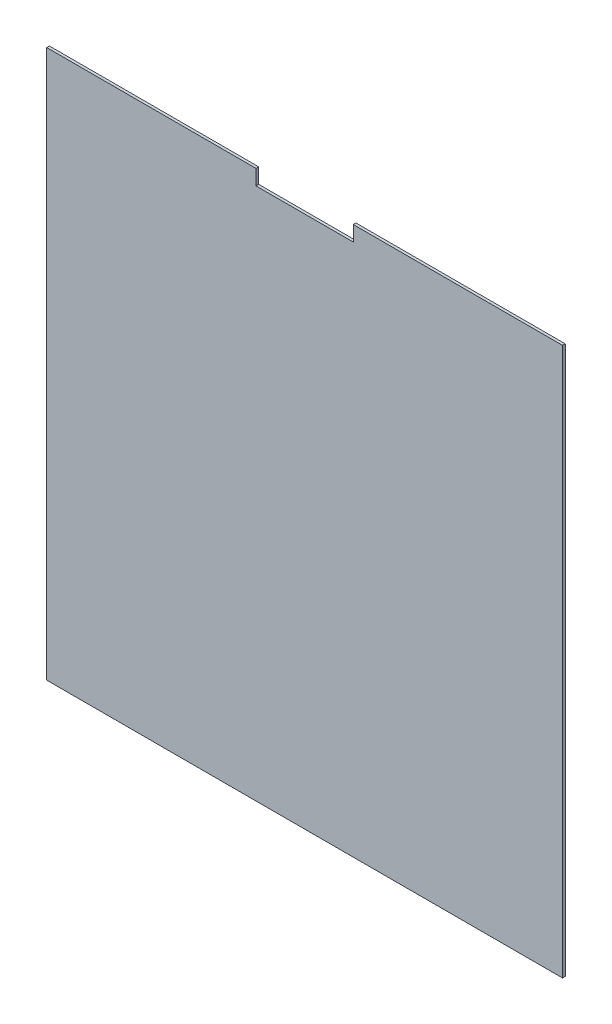
SolidWorks part; units mm, degrees
ref_plane "Front Plane" through (0, 0, 0) normal (0, 0, 1) x (1, 0, 0)
ref_plane "Top Plane" through (0, 0, 0) normal (0, 1, 0) x (1, 0, 0)
ref_plane "Right Plane" through (0, 0, 0) normal (1, 0, 0) x (0, 0, -1)
ref_plane "Plane1" through (0, 0, 5) normal (0, 0, 1) x (1, 0, 0)
sketch "Sketch1" plane through (0, 0, 5) normal (0, 0, 1) x (1, 0, 0)
  line L0 (-50, 198.7661) -> (-50, 210)
  line L1 (-50, 210) -> (-205, 210)
  line L2 (-205, 210) -> (-205, -225)
  line L3 (-205, -225) -> (177, -225)
  line L4 (177, -225) -> (177, 210)
  line L5 (177, 210) -> (22, 210)
  line L6 (22, 210) -> (22, 198.7661)
  line L7 (22, 198.7661) -> (-50, 198.7661)
  dimension "D1" = 382
  dimension "D2" = 435
  dimension "D3" = 155
  dimension "D4" = 155
extrude "Boss-Extrude1" add sketch "Sketch1" against normal blind 2
sketch "Sketch2" plane through (0, -225, 0) normal (0, -1, 0) x (1, 0, 0)
  line L4 (177, 5) -> (-205, 5)
  line L5 (-205, 5) -> (-205, 3)
  line L6 (-205, 3) -> (177, 3)
  line L7 (177, 3) -> (177, 5)
  line L8 (177, 5) -> (-205, 5)
  line L9 (-205, 5) -> (-205, 3)
  line L10 (-205, 3) -> (177, 3)
  line L11 (177, 3) -> (177, 5)
  dimension "D1" = 0
extrude "Cut-Extrude1" cut sketch "Sketch2" against normal up to surface (29.2454 mm away)
